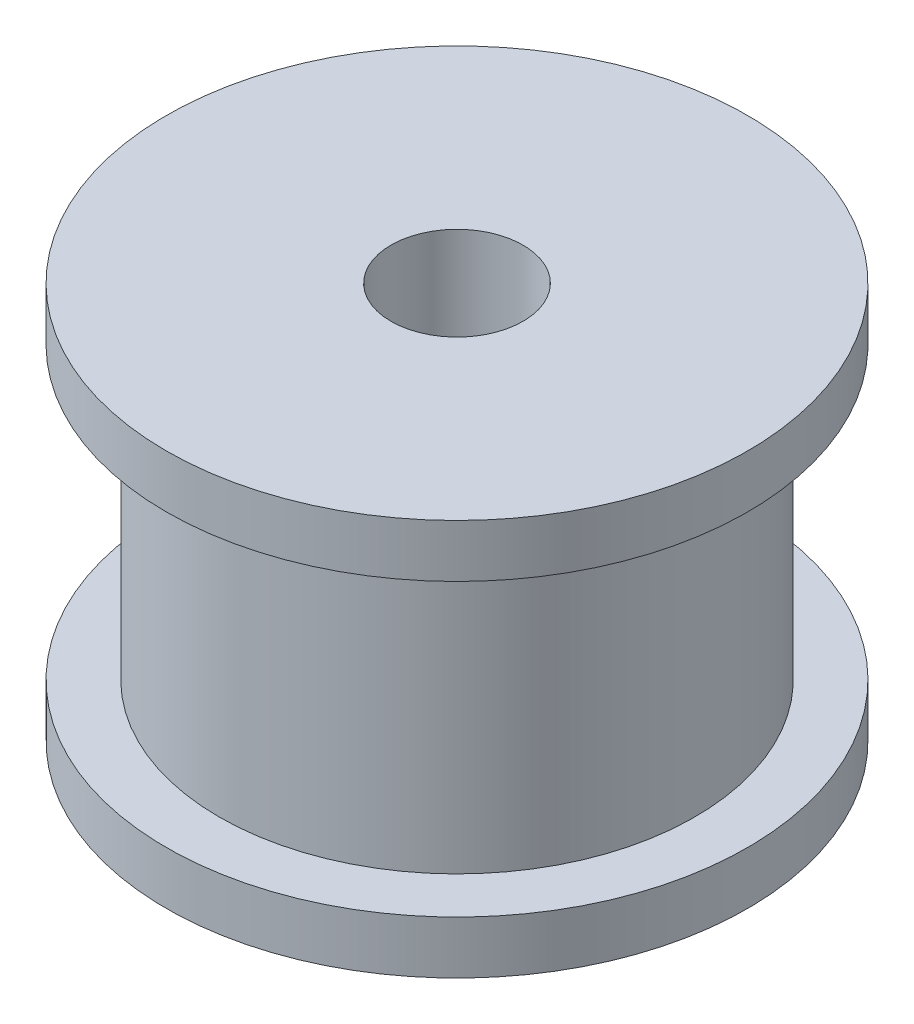
SolidWorks part; units mm, degrees
material "1060 合金"
ref_plane "前视基准面" through (0, 0, 0) normal (0, 0, 1) x (1, 0, 0)
ref_plane "上视基准面" through (0, 0, 0) normal (0, 1, 0) x (1, 0, 0)
ref_plane "右视基准面" through (0, 0, 0) normal (1, 0, 0) x (0, 0, -1)
other "Configuration Table"
sketch "草图1" plane through (0, 0, 0) normal (0, 1, 0) x (1, 0, 0)
  circle A0 centre (0, 0) radius 9
  dimension "D1" = 18
extrude "凸台-拉伸1" add sketch "草图1" against normal blind 11
sketch "草图3" plane through (0, -11, 0) normal (0, -1, 0) x (1, 0, 0)
  circle A1 centre (0, 0) radius 11
sketch "草图4" plane through (0, 0, 0) normal (0, 1, 0) x (1, 0, 0)
  circle A0 centre (0, 0) radius 11
extrude "凸台-拉伸3" add sketch "草图4" along normal blind 2
extrude "凸台-拉伸4" add sketch "草图3" along normal blind 2
sketch "草图5" plane through (0, 2, 0) normal (0, 1, 0) x (1, 0, 0)
  circle A0 centre (0, 0) radius 2.5
extrude "切除-拉伸2" cut sketch "草图5" against normal blind 22
